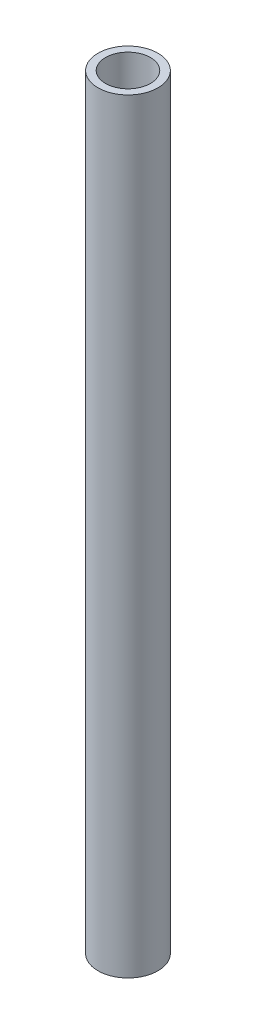
SolidWorks part; units mm, degrees
material "Сталь 08Х21Н5Т ГОСТ 5632-72"
ref_plane "Спереди" through (0, 0, 0) normal (0, 0, 1) x (1, 0, 0)
ref_plane "Сверху" through (0, 0, 0) normal (0, 1, 0) x (1, 0, 0)
ref_plane "Справа" through (0, 0, 0) normal (1, 0, 0) x (0, 0, -1)
other "Configuration Table"
sketch "Эскиз1" plane through (0, 0, 0) normal (0, 1, 0) x (1, 0, 0)
  circle A0 centre (0, 0) radius 4
  circle A1 centre (0, 0) radius 3
  dimension "D1" = 6
  dimension "D2" = 8
extrude "Бобышка-Вытянуть1" add sketch "Эскиз1" along normal blind 102
